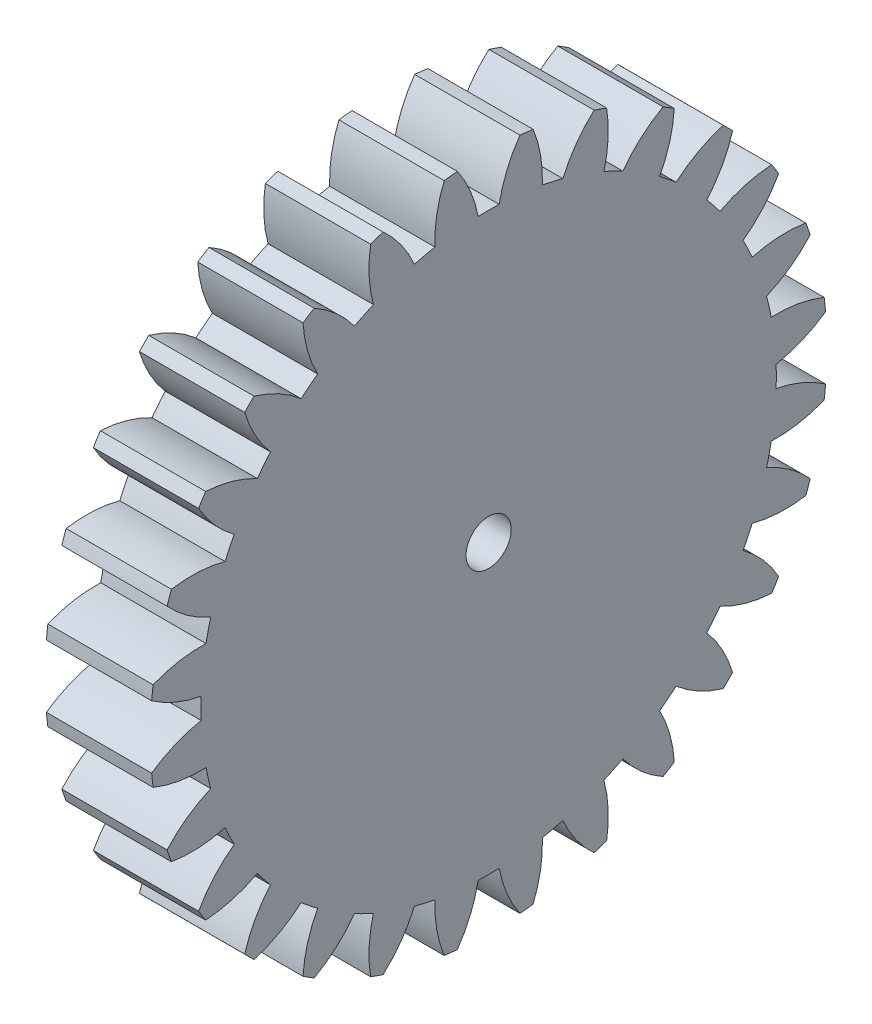
SolidWorks part; units mm, degrees
ref_plane "Plane1" through (0, 0, 0) normal (0, 0, 1) x (1, 0, 0)
ref_plane "Plane2" through (0, 0, 0) normal (0, 1, 0) x (1, 0, 0)
ref_plane "Plane3" through (0, 0, 0) normal (1, 0, 0) x (0, 0, -1)
sketch "HoldingSke" plane through (0, 0, 0) normal (0, 1, 0) x (1, 0, 0)
  line L0 (0, 0) -> (0.5886, -0.313)
  line L1 (-15, 0) -> (100, 0) construction
  line L2 (0, 0) -> (-2.1039, 2.3779)
  line L3 (0, 0) -> (-11.863, 4.5341)
  line L4 (0, 0) -> (7.6251, 4.0544)
  line L5 (0, 0) -> (-46.8476, -17.4728)
  line L6 (0, 0) -> (-5.8027, -3.9151)
  line L7 (-2.1039, 2.3779) -> (8.6586, 51.2059)
  line L8 (-76.2, 54.61) -> (-75.7, 54.61)
  line L9 (-71.009, 38.7566) -> (-53.1078, 45.2721)
  line L10 (-76.2, 71.12) -> (104.1128, 71.12)
  line L11 (0, 0) -> (-7, 0)
  line L12 (-76.2, 101.6) -> (-76.147, 101.6)
  line L13 (24.9733, 27.94) -> (52.9518, 28.4284)
  line L14 (24.9733, 27.94) -> (24.9743, 27.94)
  line L15 (24.9733, 27.94) -> (100.4006, 29.5858)
  line L16 (-63.627, -1.5) -> (-12.827, -1.5)
  circle A0 centre (0, 0) radius 1.5
  circle A1 centre (0, 0) radius 19.124
  circle A2 centre (0, 0) radius 37.5
  circle A3 centre (0, 0) radius 1.5
  dimension "MHD" = 38.248
  dimension "Hub_dia" = 75
  dimension "Bore" = 3
  dimension "MBD" = 3
  dimension "Num_teeth" = 28
  dimension "Pitch" = 0.6667
  dimension "Overall_len" = 50
  dimension "Show_teeth" = 28
  dimension "Thickness" = 7
  dimension "OAL" = 50.0001
  dimension "T_dim" = 0.5
  dimension "Ap" = 20
  dimension "H" = 19.05
  dimension "Pitch_radius" = 180.3128
  dimension "Width" = 7
  dimension "Backlash" = 0.053
  dimension "Addendum_fac" = 1
  dimension "Dedendum_fac" = 1.25
  dimension "Clearance_fac" = 0.25
  dimension "Dedendum_add" = 0.001
  dimension "Module" = 1.5
sketch "BasProSke" plane through (0, 0, 0) normal (0, 1, 0) x (1, 0, 0)
  line L0 (-10, 0) -> (60, 0) construction
  line L1 (0, 0) -> (0, 22.5)
  line L2 (0, 0) -> (7, 0)
  line L3 (7, 0) -> (7, 22.5)
  line L4 (7, 22.5) -> (0, 22.5)
  dimension "Thickness" = 7
  dimension "Diameter" = 45
revolve "Base-Revolve" add sketch "BasProSke" angle 360 about L0
sketch "TooCutSke" plane through (0, 0, 0) normal (1, 0, 0) x (0, 0, -1)
  line L1 (0, 0) -> (0, 107) construction
  line L2 (0, 0) -> (-1.2702, 20.9615) construction
  line L3 (0, 0) -> (-4.6962, 41.6802) construction
  line L4 (-1.2702, 20.9615) -> (-2.3481, 20.8401) construction
  arc A0 (0.7007, 19.1112) -> (-0.7007, 19.1112) centre (0, 0) ccw
  arc A1 (2.0988, 22.4274) -> (-2.0988, 22.4274) centre (0, 0) ccw
  circle A2 centre (0, 0) radius 21 construction
  circle A3 centre (0, 0) radius 19.7335 construction
  arc A4 (-0.7007, 19.1112) -> (-2.0988, 22.4274) centre (-8.9603, 17.5819) ccw
  arc A5 (2.0988, 22.4274) -> (0.7007, 19.1112) centre (8.9603, 17.5819) ccw
  dimension "Root_dia" = 38.248
  dimension "Overcut_dia" = 45.0508
  dimension "Pitch_dia" = 42
  dimension "Base_dia" = 39.4671
  dimension "Flank_rad" = 8.4
  dimension "Half_ang" = 6.429
  dimension "Half_CT" = 1.0847
extrude "ToothCut" cut sketch "TooCutSke" along normal through all
fillet "Breaks" [suppressed] radius 0.03
fillet "RootFillets" [suppressed] radius 0.376
pattern_circular "TeethCuts" count 28 every 12.857 about axis through (-10, 0, 0) along (1, 0, 0) of "ToothCut", "RootFillets", "Breaks"
sketch "HubNeaOneSke" plane through (0, 0, 0) normal (-1, 0, 0) x (0, 0, 1)
  circle A0 centre (0, 0) radius 19.124
  dimension "Diameter" = 38.248
extrude "HubNearOne" [suppressed] add sketch "HubNeaOneSke" along normal blind 43.0001
sketch "HubNeaBotSke" plane through (0, 0, 0) normal (-1, 0, 0) x (0, 0, 1)
  circle A0 centre (0, 0) radius 19.124
  dimension "Diameter" = 38.248
extrude "HubNearBoth" [suppressed] add sketch "HubNeaBotSke" along normal blind 21.5
ref_plane "FarPln" through (7, 0, 0) normal (1, 0, 0) x (0, 0, -1)
sketch "HubFarSke" plane through (7, 0, 0) normal (1, 0, 0) x (0, 0, -1)
  circle A0 centre (0, 0) radius 19.124
  dimension "Diameter" = 38.248
extrude "HubFar" [suppressed] add sketch "HubFarSke" along normal blind 21.5
sketch "BorSke" plane through (0, 0, 0) normal (1, 0, 0) x (0, 0, -1)
  circle A0 centre (0, 0) radius 1.5
  dimension "Diameter" = 3
extrude "Bore" cut sketch "BorSke" along normal mid plane 100.0001
sketch "KeySke" plane through (0, 0, 0) normal (1, 0, 0) x (0, 0, -1)
  line L0 (-0.6, 0) -> (-0.6, 2)
  line L1 (-0.6, 2) -> (0.6, 2)
  line L2 (0.6, 2) -> (0.6, 0)
  line L3 (0, 0) -> (0, 34) construction
  line L4 (-0.6, 0) -> (0.6, 0)
  dimension "Offset" = 2
  dimension "Width" = 1.2
extrude "Keyway" [suppressed] cut sketch "KeySke" along normal mid plane 100.0001
pattern_circular "Keyway2" [suppressed] count 2 every 90 about axis through (-10, 0, 0) along (1, 0, 0)
equation "' \"Module@HoldingSke\" = 6.35"
equation "' \"Num_teeth@HoldingSke\" = 12"
equation "' \"Ap@HoldingSke\" =  20"
equation "' \"Ap@HoldingSke\" = 20"
equation "' \"Width@HoldingSke\" = 0.5 * 25.4"
equation "' \"Hub_dia@HoldingSke\"= 1 * 25.4"
equation "' \"Hub_dia@HoldingSke\" = 1 * 25.4"
equation "' \"Overall_len@HoldingSke\" = 1.0 * 25.4"
equation "' \"Bore@HoldingSke\" = 0.75 * 25.4"
equation "' \"T_dim@HoldingSke\" = 0.1 * 25.4"
equation "' \"Width@KeySke\" = 0.25 * 25.4"
equation "' \"Show_teeth@HoldingSke\" = 13"
equation "' \"Backlash@HoldingSke\" = 0.009 * 25.4"
equation "' \"Addendum_fac@HoldingSke\" = 1.0"
equation "' \"Dedendum_fac@HoldingSke\" = 1.25"
equation "' \"Dedendum_add@HoldingSke\" = 0.00005 * 25.4"
equation "' \"Clearance_fac@HoldingSke\" = 0.25"
equation "\"Pitch@HoldingSke\" = 1 / \"Module@HoldingSke\""
equation "\"Overcut_dia@TooCutSke\" = (\"Num_teeth@HoldingSke\" + 2 * \"Addendum_fac@HoldingSke\") / \"Pitch@HoldingSke\" + 0.002 * 25.4"
equation "\"Pitch_dia@TooCutSke\" = \"Num_teeth@HoldingSke\" / \"Pitch@HoldingSke\""
equation "\"Base_dia@TooCutSke\" = \"Num_teeth@HoldingSke\" / \"Pitch@HoldingSke\" * cos((\"Ap@HoldingSke\"  * 3.14159265 / 180))"
equation "\"Root_dia@TooCutSke\" = (\"Num_teeth@HoldingSke\" + 2) / \"Pitch@HoldingSke\" - 2 * (\"Addendum_fac@HoldingSke\" + \"Dedendum_fac@HoldingSke\") / \"Pitch@HoldingSke\" - \"Dedendum_add@HoldingSke\" * 2"
equation "\"Half_ang@TooCutSke\" = 180 / \"Num_teeth@HoldingSke\""
equation "\"Half_CT@TooCutSke\" = \"Num_teeth@HoldingSke\" / \"Pitch@HoldingSke\" * sin((3.14159265 / 2 / \"Num_teeth@HoldingSke\")) / 2 - 7 * \"Backlash@HoldingSke\" / 4"
equation "\"Flank_rad@TooCutSke\" = \"Num_teeth@HoldingSke\" / \"Pitch@HoldingSke\" / 5"
equation "\"Radius@RootFillets\" = \"Clearance_fac@HoldingSke\" / \"Pitch@HoldingSke\" + \"Dedendum_add@HoldingSke\""
equation "\"Break_rad@Breaks\" = 0.02 / \"Pitch@HoldingSke\""
equation "\"Thickness@HoldingSke\" = \"Width@HoldingSke\""
equation "\"OAL@HoldingSke\" = \"Thickness@HoldingSke\""
equation "\"MHD@HoldingSke\" = (\"Num_teeth@HoldingSke\" + 2) / \"Pitch@HoldingSke\" - 2 * (\"Addendum_fac@HoldingSke\" + \"Dedendum_fac@HoldingSke\")  / \"Pitch@HoldingSke\" - \"Dedendum_add@HoldingSke\" * 2"
equation "\"MBD@HoldingSke\" = (\"Num_teeth@HoldingSke\" + 2) / \"Pitch@HoldingSke\" - 2 * (\"Addendum_fac@HoldingSke\" + \"Dedendum_fac@HoldingSke\")  / \"Pitch@HoldingSke\" - \"Dedendum_add@HoldingSke\" * 2 - 0.002 * 25.4"
equation "\"MHD@HoldingSke\" = ((sgn( \"MHD@HoldingSke\" - \"Hub_dia@HoldingSke\" )-1)*( \"MHD@HoldingSke\" - \"Hub_dia@HoldingSke\" ))/-2+ \"Hub_dia@HoldingSke\""
equation "\"MBD@HoldingSke\" = ((sgn( \"MBD@HoldingSke\" - \"Bore@HoldingSke\" )-1)*( \"MBD@HoldingSke\" - \"Bore@HoldingSke\" ))/-2+ \"Bore@HoldingSke\""
equation "\"OAL@HoldingSke\" = ((sgn( \"OAL@HoldingSke\" - \"Overall_len@HoldingSke\" )+1)*( \"OAL@HoldingSke\" - \"Overall_len@HoldingSke\" ))/2 + \"Overall_len@HoldingSke\" + 0.000002 * 25.4"
equation "\"Num_teeth@TeethCuts\" = int( \"Show_teeth@HoldingSke\" ) + 1"
equation "\"Num_teeth@TeethCuts\" = ((sgn( \"Num_teeth@TeethCuts\" - \"Num_teeth@HoldingSke\" )-1)*( \"Num_teeth@TeethCuts\" - \"Num_teeth@HoldingSke\" ))/-2+ \"Num_teeth@HoldingSke\""
equation "\"Num_teeth@TeethCuts\" = ((sgn( \"Num_teeth@TeethCuts\" - 2.0)+1)*( \"Num_teeth@TeethCuts\" - 2.0))/2 +2.0"
equation "\"Angle@TeethCuts\" = 360.0 / \"Num_teeth@HoldingSke\""
equation "\"Diameter@BasProSke\" = (\"Num_teeth@HoldingSke\" + 2 * \"Addendum_fac@HoldingSke\") / \"Pitch@HoldingSke\""
equation "\"Thickness@BasProSke\"  = \"Thickness@HoldingSke\""
equation "' \"Fillet_rad@BasProSke\" =  \"Thickness@HoldingSke\" * 0.05"
equation "' \"Fillet_rad@BasProSke\" = \"Thickness@HoldingSke\" * 0.05"
equation "\"MHD@HoldingSke\" = ((sgn( \"MHD@HoldingSke\" - \"Root_dia@TooCutSke\" )-1)*( \"MHD@HoldingSke\" - \"Root_dia@TooCutSke\" ))/-2+ \"Root_dia@TooCutSke\""
equation "\"Diameter@HubNeaOneSke\" = \"MHD@HoldingSke\""
equation "\"Length@HubNearOne\" = \"OAL@HoldingSke\" - \"Thickness@BasProSke\""
equation "\"Diameter@HubNeaBotSke\" = \"MHD@HoldingSke\""
equation "\"Length@HubNearBoth\" = ( \"OAL@HoldingSke\" - \"Thickness@BasProSke\" ) / 2.0"
equation "\"Thickness@FarPln\" = \"Thickness@BasProSke\""
equation "\"Diameter@HubFarSke\" = \"MHD@HoldingSke\""
equation "\"Length@HubFar\" = ( \"OAL@HoldingSke\" - \"Thickness@BasProSke\" ) / 2.0"
equation "\"Diameter@BorSke\" = \"MBD@HoldingSke\""
equation "\"D1@Bore\" = \"OAL@HoldingSke\" * 2.0"
equation "\"D1@Keyway\" = \"OAL@HoldingSke\" * 2.0"
equation "\"Offset@KeySke\" = \"T_dim@HoldingSke\" + \"MBD@HoldingSke\" / 2.0"
